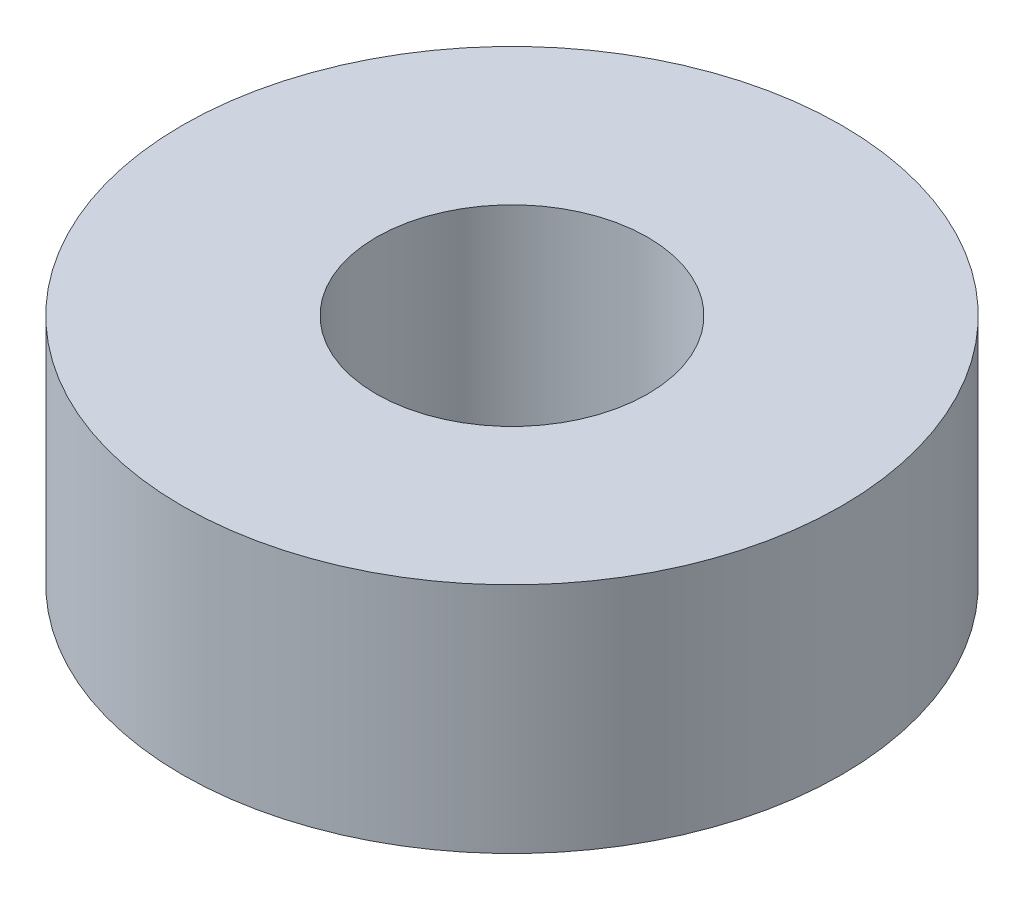
SolidWorks part; units mm, degrees
ref_plane "前视基准面" through (0, 0, 0) normal (0, 0, 1) x (1, 0, 0)
ref_plane "上视基准面" through (0, 0, 0) normal (0, 1, 0) x (1, 0, 0)
ref_plane "右视基准面" through (0, 0, 0) normal (1, 0, 0) x (0, 0, -1)
sketch "草图1" plane through (0, 0, 0) normal (0, 1, 0) x (1, 0, 0)
  circle A0 centre (0, 0) radius 8.5
  circle A1 centre (0, 0) radius 3.5
  dimension "D1" = 7
  dimension "D2" = 17
extrude "凸台-拉伸1" add sketch "草图1" along normal blind 6
